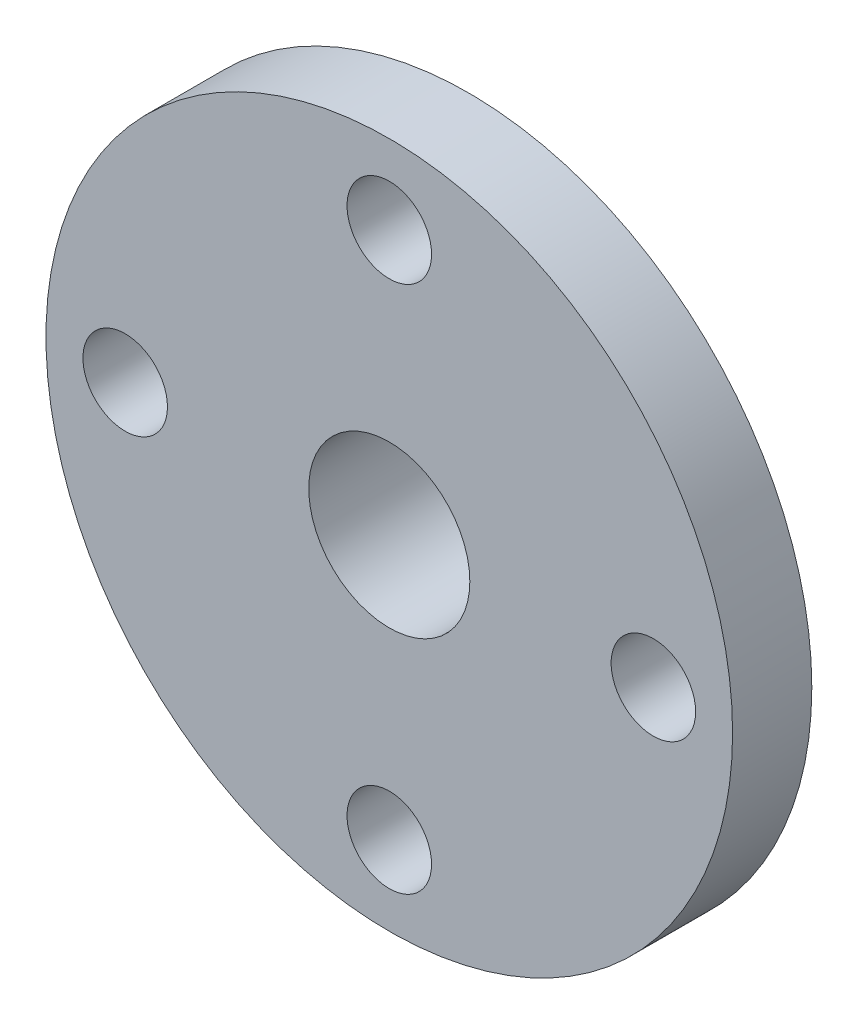
SolidWorks part; units mm, degrees
ref_plane "Front Plane" through (0, 0, 0) normal (0, 0, 1) x (1, 0, 0)
ref_plane "Top Plane" through (0, 0, 0) normal (0, 1, 0) x (1, 0, 0)
ref_plane "Right Plane" through (0, 0, 0) normal (1, 0, 0) x (0, 0, -1)
sketch "Horn_plate_envelope_profile" plane through (0, 0, 0) normal (0, 0, 1) x (1, 0, 0)
  circle A0 centre (0, 0) radius 13
  circle A1 centre (0, 0) radius 3.05
  dimension "D1" = 26
  dimension "D2" = 6.1
extrude "Horn_plate_envelope" add sketch "Horn_plate_envelope_profile" along normal blind 3
sketch "Spline_hub_envelope_profile" plane through (0, 0, 0) normal (0, 0, 1) x (1, 0, 0)
  circle A0 centre (0, 0) radius 4.5
  circle A1 centre (0, 0) radius 3.05
  dimension "D1" = 9
  dimension "D2" = 6.1
extrude "Spline_hub_envelope" add sketch "Spline_hub_envelope_profile" along normal blind 4 from offset 4
sketch "Nominal_horn_attachment_holes_profile" plane through (0, 0, 0) normal (0, 0, 1) x (1, 0, 0)
  circle A0 centre (-10, 0) radius 1.6
  circle A1 centre (10, 0) radius 1.6
  circle A2 centre (0, -10) radius 1.6
  circle A3 centre (0, 10) radius 1.6
  dimension "D1" = 3.2
  dimension "D2" = 3.2
  dimension "D3" = 3.2
  dimension "D4" = 3.2
extrude "Nominal_horn_attachment_holes" cut sketch "Nominal_horn_attachment_holes_profile" along normal through all from offset 50
